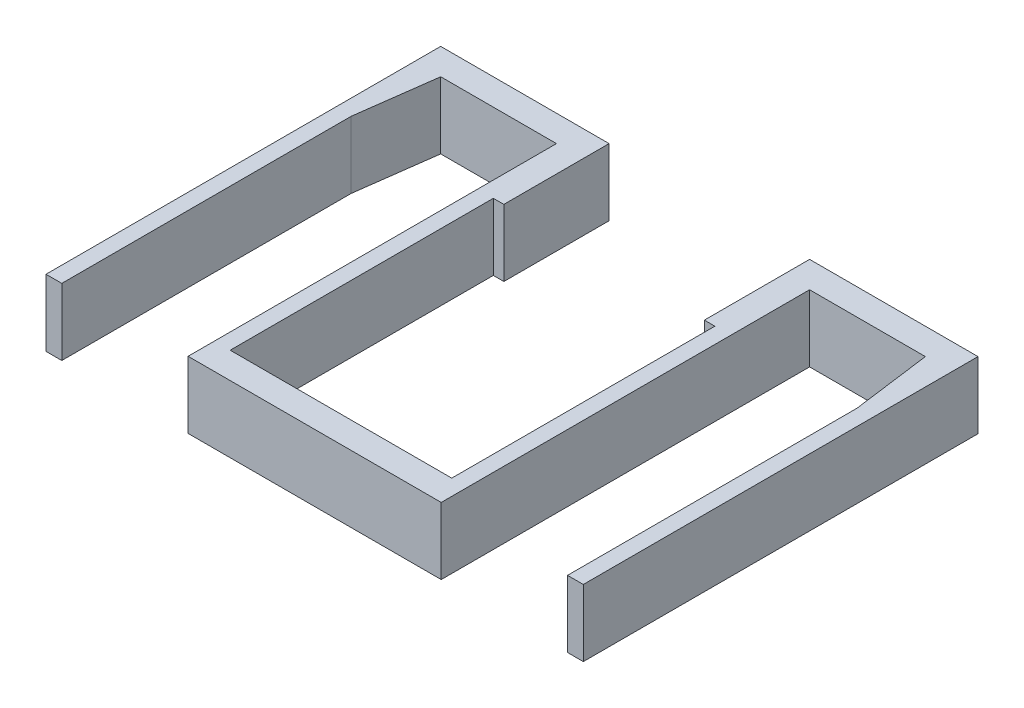
SolidWorks part; units mm, degrees
material "PE High Density"
ref_plane "Front Plane" through (0, 0, 0) normal (0, 0, 1) x (1, 0, 0)
ref_plane "Top Plane" through (0, 0, 0) normal (0, 1, 0) x (1, 0, 0)
ref_plane "Right Plane" through (0, 0, 0) normal (1, 0, 0) x (0, 0, -1)
sketch "Sketch1" plane through (0, 0, 0) normal (0, 1, 0) x (1, 0, 0)
  line L0 (-92.1, 130) -> (-96.1, 100)
  line L1 (38.1, 100) -> (38.1, 140)
  line L2 (38.1, 140) -> (102.1, 140)
  line L3 (102.1, 140) -> (102.1, -10)
  line L4 (92.1, 130) -> (96.1, 100)
  line L5 (-96.1, 100) -> (-96.1, -10)
  line L6 (92.1, 130) -> (48.1, 130)
  line L7 (48.1, 130) -> (48.1, -10)
  line L8 (48.1, -10) -> (-48.1, -10)
  line L9 (96.1, 100) -> (96.1, -10)
  line L10 (-42.1, 0) -> (42.1, 0)
  line L11 (42.1, 0) -> (42.1, 100)
  line L12 (96.1, -10) -> (102.1, -10)
  line L14 (-42.1, 0) -> (-42.1, 100)
  line L15 (-48.1, 130) -> (-48.1, -10)
  line L16 (-92.1, 130) -> (-48.1, 130)
  line L18 (-102.1, -10) -> (-96.1, -10)
  line L19 (-102.1, 140) -> (-102.1, -10)
  line L20 (-38.1, 140) -> (-102.1, 140)
  line L21 (-38.1, 100) -> (-38.1, 140)
  line L24 (38.1, 100) -> (42.1, 100)
  line L26 (-38.1, 100) -> (-42.1, 100)
  point P0 (99.275, 94.7436)
  point P2 (0, 0)
  point P31 (0, -10)
  dimension "D1" = 10
  dimension "D2" = 6
  dimension "D3" = 140
  dimension "D4" = 10
  dimension "D5" = 76.2
  dimension "D6" = 10
  dimension "D7" = 6
  dimension "D8" = 10
  dimension "D9" = 40
  dimension "D10" = 48
  dimension "D11" = 30
extrude "Boss-Extrude1" add sketch "Sketch1" along normal mid plane 25.4
